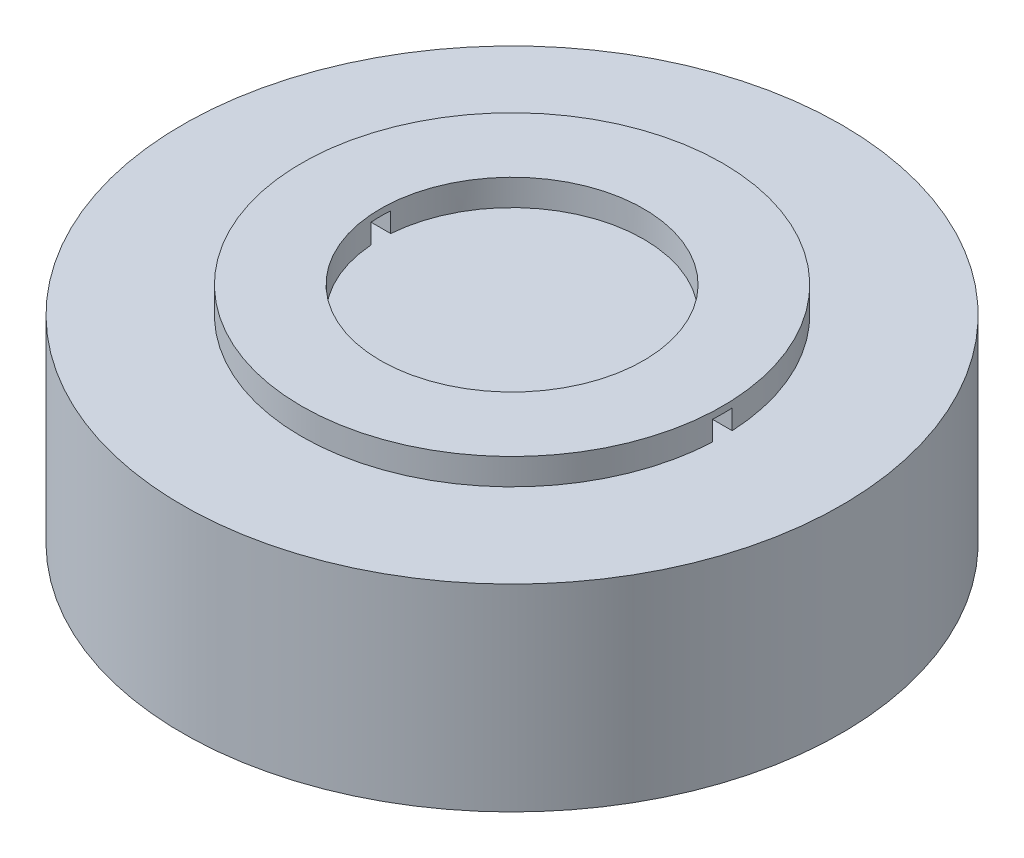
SolidWorks part; units mm, degrees
ref_plane "前视基准面" through (0, 0, 0) normal (0, 0, 1) x (1, 0, 0)
ref_plane "上视基准面" through (0, 0, 0) normal (0, 1, 0) x (1, 0, 0)
ref_plane "右视基准面" through (0, 0, 0) normal (1, 0, 0) x (0, 0, -1)
sketch "草图1" plane through (0, 0, 0) normal (0, 1, 0) x (1, 0, 0)
  circle A0 centre (0, 0) radius 16
  dimension "D1" = 32
extrude "凸台-拉伸1" add sketch "草图1" against normal blind 2 contours A0
sketch "草图2" plane through (0, -2, 0) normal (0, -1, 0) x (1, 0, 0)
  circle A0 centre (0, 0) radius 25.05
  dimension "D1" = 50.1
extrude "凸台-拉伸2" add sketch "草图2" along normal blind 15
sketch "草图4" plane through (0, -17, 0) normal (0, -1, 0) x (1, 0, 0)
  circle A0 centre (0, 0) radius 2
  dimension "D1" = 4
extrude "切除-拉伸1" cut sketch "草图4" against normal blind 10
sketch "草图6" plane through (0, -2, 0) normal (0, 1, 0) x (1, 0, 0)
  line L1 (-30, 0.75) -> (30, 0.75)
  line L2 (-30, 0.75) -> (-30, -0.75)
  line L3 (-30, -0.75) -> (30, -0.75)
  line L4 (30, 0.75) -> (30, -0.75)
  line L5 (-30, 0.75) -> (30, -0.75) construction
  line L6 (-30, -0.75) -> (30, 0.75) construction
  point P0 (0, 0)
  dimension "D1" = 1.5
  dimension "D2" = 60
extrude "切除-拉伸2" cut sketch "草图6" along normal blind 1.5
sketch "草图8" plane through (0, 0, 0) normal (0, 1, 0) x (1, 0, 0)
  circle A0 centre (0, 0) radius 10
  dimension "D1" = 20
extrude "切除-拉伸3" cut sketch "草图8" against normal blind 2
